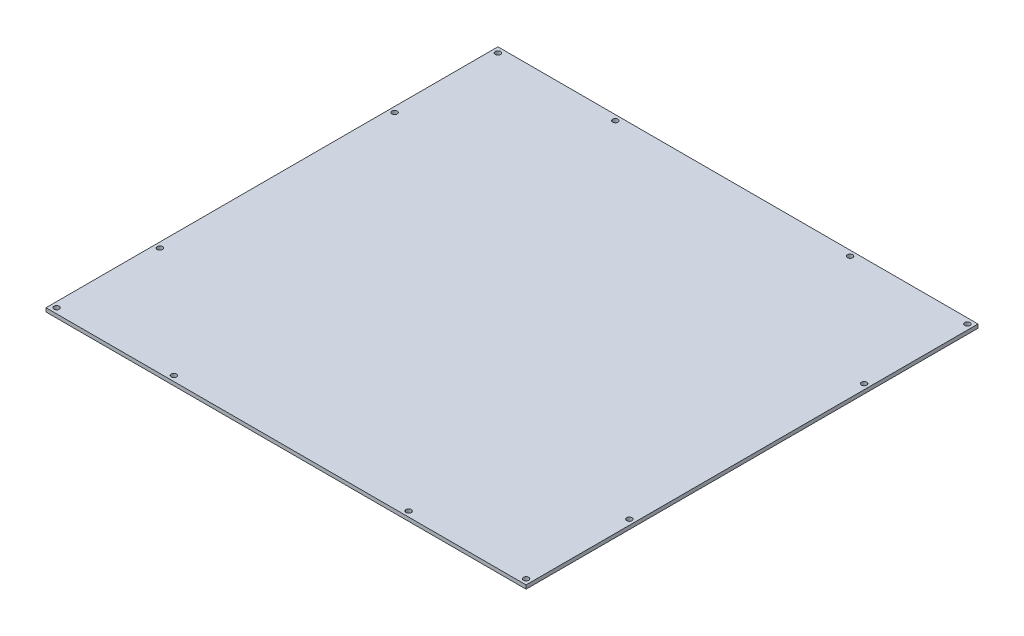
SolidWorks part; units mm, degrees
ref_plane "Front Plane" through (0, 0, 0) normal (0, 0, 1) x (1, 0, 0)
ref_plane "Top Plane" through (0, 0, 0) normal (0, 1, 0) x (1, 0, 0)
ref_plane "Right Plane" through (0, 0, 0) normal (1, 0, 0) x (0, 0, -1)
sketch "Sketch1" plane through (0, 0, 0) normal (0, 1, 0) x (1, 0, 0)
  line L1 (-204.5, -192.5) -> (204.5, -192.5)
  line L2 (-204.5, -192.5) -> (-204.5, 192.5)
  line L3 (-204.5, 192.5) -> (204.5, 192.5)
  line L4 (204.5, -192.5) -> (204.5, 192.5)
  line L5 (-204.5, -192.5) -> (204.5, 192.5) construction
  line L6 (-204.5, 192.5) -> (204.5, -192.5) construction
  point P0 (0, 0)
  dimension "D1" = 409
  dimension "D2" = 385
extrude "Boss-Extrude1" add sketch "Sketch1" along normal blind 3.175
hole_wizard "M4 Clearance Hole1" positions "Sketch2" profile "Sketch4" hole size "M4" standard "ANSI Metric" end condition through all
sketch "Sketch2" plane through (0, 3.175, 0) normal (0, 1, 0) x (1, 0, 0)
  line L0 (204.5, 192.5) -> (-204.5, 192.5) construction
  line L1 (-204.5, 192.5) -> (-204.5, -192.5) construction
  line L2 (-200, 100) -> (-200, -100)
  line L3 (0, -55) -> (0, 55) construction
  line L4 (200, 100) -> (200, -100)
  line L5 (-100, 188) -> (100, 188)
  line L6 (-55, 0) -> (55, 0) construction
  line L7 (-100, -188) -> (100, -188)
  point P0 (-200, 188)
  point P7 (-200, 100)
  point P8 (-200, -100)
  point P10 (-200, 0)
  point P21 (200, -100)
  point P22 (200, 100)
  point P23 (200, 188)
  point P24 (-100, 188)
  point P25 (100, 188)
  point P33 (0, 188)
  point P38 (100, -188)
  point P39 (-100, -188)
  point P40 (200, -188)
  point P41 (-200, -188)
  dimension "D1" = 4.5
  dimension "D2" = 4.5
  dimension "D3" = 200
  dimension "D4" = 200
sketch "Sketch4" plane through (-200, 3.175, -188) normal (1, 0, 0) x (0, 0, 1)
  line L0 (0, 0) -> (0, 3.175)
  line L1 (0, 3.175) -> (2.25, 3.175)
  line L2 (2.25, 3.175) -> (2.25, 0)
  line L5 (2.25, 0) -> (0, 0)
  line L11 (0, -6.35) -> (0, 107.95) construction
  dimension "Thru Hole Dia." = 4.5
  dimension "Thru Hole Depth" = 3.175
